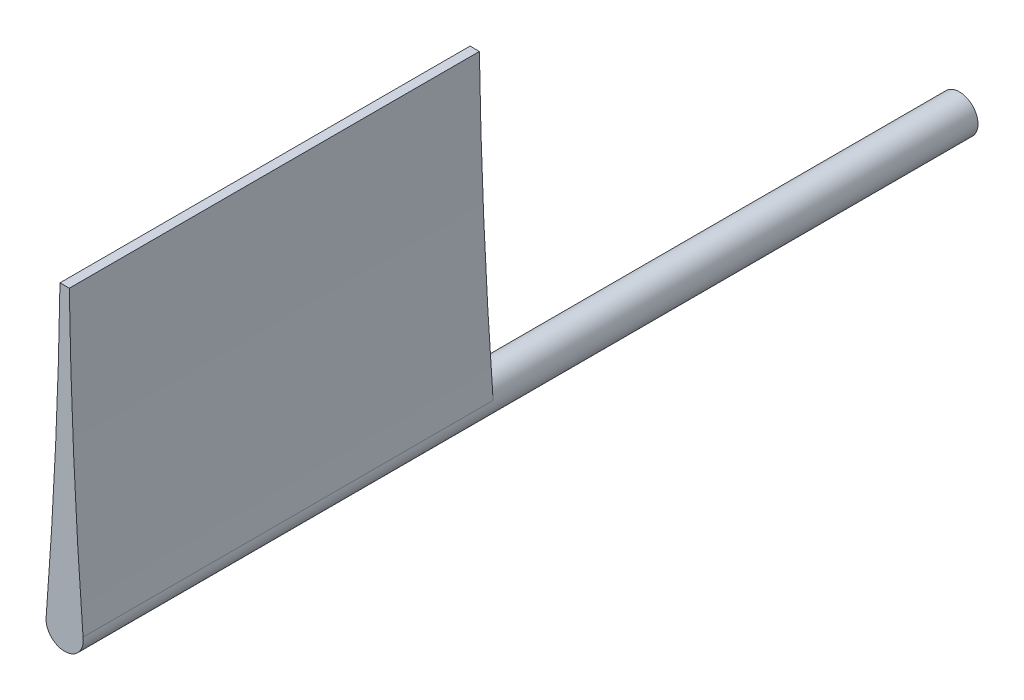
SolidWorks part; units mm, degrees
ref_plane "Front Plane" through (0, 0, 0) normal (0, 0, 1) x (1, 0, 0)
ref_plane "Top Plane" through (0, 0, 0) normal (0, 1, 0) x (1, 0, 0)
ref_plane "Right Plane" through (0, 0, 0) normal (1, 0, 0) x (0, 0, -1)
sketch "Sketch1" plane through (0, 0, 0) normal (0, 1, 0) x (1, 0, 0)
  line L0 (0, 25.6061) -> (-10, 25.6061)
  line L1 (-10, 25.6061) -> (-10, -84.3939)
  line L2 (-10, -84.3939) -> (0, -84.3939)
  line L3 (0, -84.3939) -> (0, 25.6061)
  dimension "D1" = 10
  dimension "D2" = 110
ref_plane "Plane1" through (0, 40, 0) normal (0, 1, 0) x (1, 0, 0)
sketch "Sketch2" plane through (0, 40, 0) normal (0, 1, 0) x (1, 0, 0)
  line L0 (-5, 25.6061) -> (-2.5, 25.6061) construction
  line L1 (0, 25.6061) -> (-10, 25.6061) construction
  line L2 (-2.5, 25.6061) -> (-2.5, -84.3939)
  line L3 (-10, -84.3939) -> (0, -84.3939) construction
  line L4 (-2.5, -84.3939) -> (-7.5, -84.3939)
  line L5 (-2.5, 25.6061) -> (-7.5, 25.6061)
  line L6 (-5, -84.3939) -> (-5, -69.5999) construction
  line L7 (-7.5, 25.6061) -> (-7.5, -84.3939)
  dimension "D1" = 2.5
ref_plane "Plane2" through (0, 80, 0) normal (0, 1, 0) x (1, 0, 0)
sketch "Sketch3" plane through (0, 80, 0) normal (0, 1, 0) x (1, 0, 0)
  line L0 (-6.25, 25.6061) -> (-3.75, 25.6061)
  line L1 (0, 25.6061) -> (-10, 25.6061) construction
  line L2 (-5, 25.6061) -> (-5, 21.6961) construction
  line L3 (-3.75, 25.6061) -> (-3.75, -84.3939)
  line L4 (-10, -84.3939) -> (0, -84.3939) construction
  line L5 (-3.75, -84.3939) -> (-6.25, -84.3939)
  line L6 (-6.25, 25.6061) -> (-6.25, -84.3939)
  point P13 (-5, -84.3939)
loft "Loft1" add profiles "Sketch1", "Sketch2", "Sketch3"
sketch "Sketch4" plane through (0, 0, -25.6061) normal (0, 0, -1) x (-1, 0, 0)
  line L0 (10, 0) -> (0, 0) construction
  circle A0 centre (5, 0) radius 5
extrude "Boss-Extrude1" add sketch "Sketch4" along normal blind 130
sketch "Sketch5" plane through (0, 0, -25.6061) normal (0, 0, 1) x (1, 0, 0)
  line L0 (0, 0) -> (-10, 0) construction
  circle A0 centre (-5, 0) radius 5
  dimension "D1" = 10
extrude "Boss-Extrude2" add sketch "Sketch5" along normal blind 110
